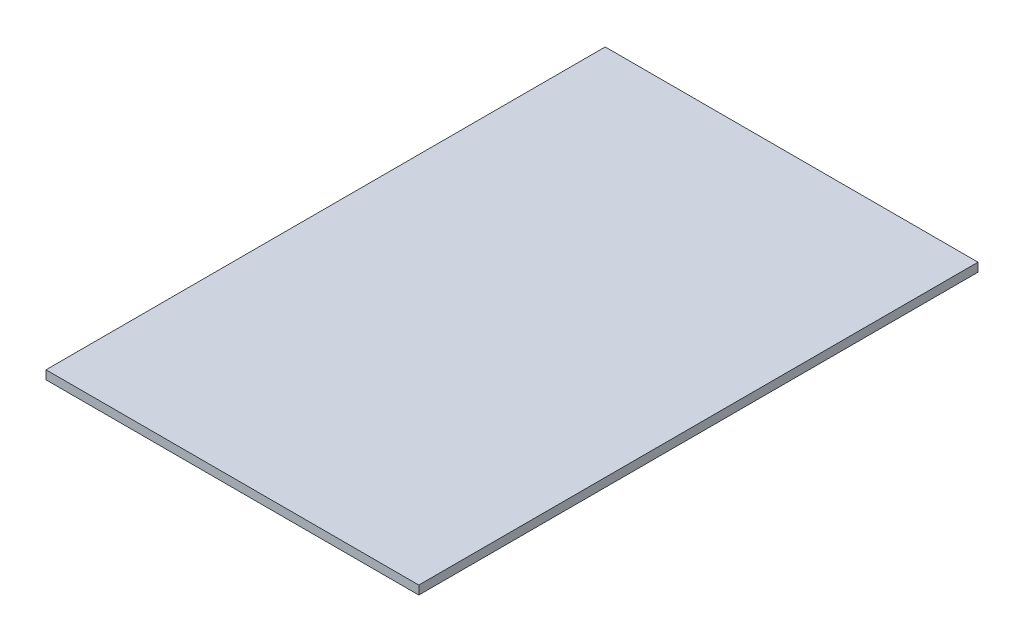
SolidWorks part; units mm, degrees
ref_plane "Front Plane" through (0, 0, 0) normal (0, 0, 1) x (1, 0, 0)
ref_plane "Top Plane" through (0, 0, 0) normal (0, 1, 0) x (1, 0, 0)
ref_plane "Right Plane" through (0, 0, 0) normal (1, 0, 0) x (0, 0, -1)
sketch "Sketch1" plane through (0, 0, 0) normal (0, 1, 0) x (1, 0, 0)
  line L1 (0, 0) -> (600, 0)
  line L2 (0, 0) -> (0, 900)
  line L3 (0, 900) -> (600, 900)
  line L4 (600, 0) -> (600, 900)
  dimension "D1" = 600
  dimension "D2" = 900
extrude "Boss-Extrude1" add sketch "Sketch1" along normal blind 14
